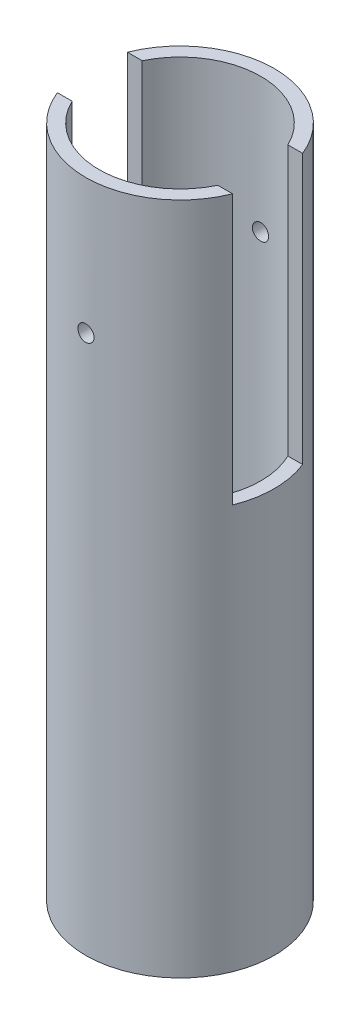
SolidWorks part; units mm, degrees
ref_plane "Plan de face" through (0, 0, 0) normal (0, 0, 1) x (1, 0, 0)
ref_plane "Plan de dessus" through (0, 0, 0) normal (0, 1, 0) x (1, 0, 0)
ref_plane "Plan de droite" through (0, 0, 0) normal (1, 0, 0) x (0, 0, -1)
sketch "Esquisse3" plane through (0, 0, 0) normal (0, 1, 0) x (1, 0, 0)
  circle A0 centre (0, 0) radius 30
  circle A1 centre (0, 0) radius 35
extrude "Boss.-Extru.3" add sketch "Esquisse3" along normal blind 250
sketch "Esquisse4" plane through (0, 250, 0) normal (0, 1, 0) x (1, 0, 0)
  line L1 (-62.095, -13) -> (62.095, -13)
  line L2 (-62.095, -13) -> (-62.095, 13)
  line L3 (-62.095, 13) -> (62.095, 13)
  line L4 (62.095, -13) -> (62.095, 13)
  line L5 (-62.095, -13) -> (62.095, 13) construction
  line L6 (-62.095, 13) -> (62.095, -13) construction
  point P0 (0, 0)
  dimension "D1" = 26
extrude "Enlèv. mat.-Extru.1" cut sketch "Esquisse4" against normal blind 100
sketch "Esquisse6" plane through (0, 0, 0) normal (0, 0, 1) x (1, 0, 0)
  line L0 (-32.4962, 150) -> (32.4962, 250) construction
  line L1 (32.4962, 250) -> (-32.4962, 250) construction
  line L2 (32.4962, 250) -> (32.4962, 150) construction
  line L3 (32.4962, 150) -> (-32.4962, 250) construction
  circle A0 centre (0, 200) radius 3
extrude "Enlèv. mat.-Extru.2" cut sketch "Esquisse6" against normal blind 100 and the other way blind 100
